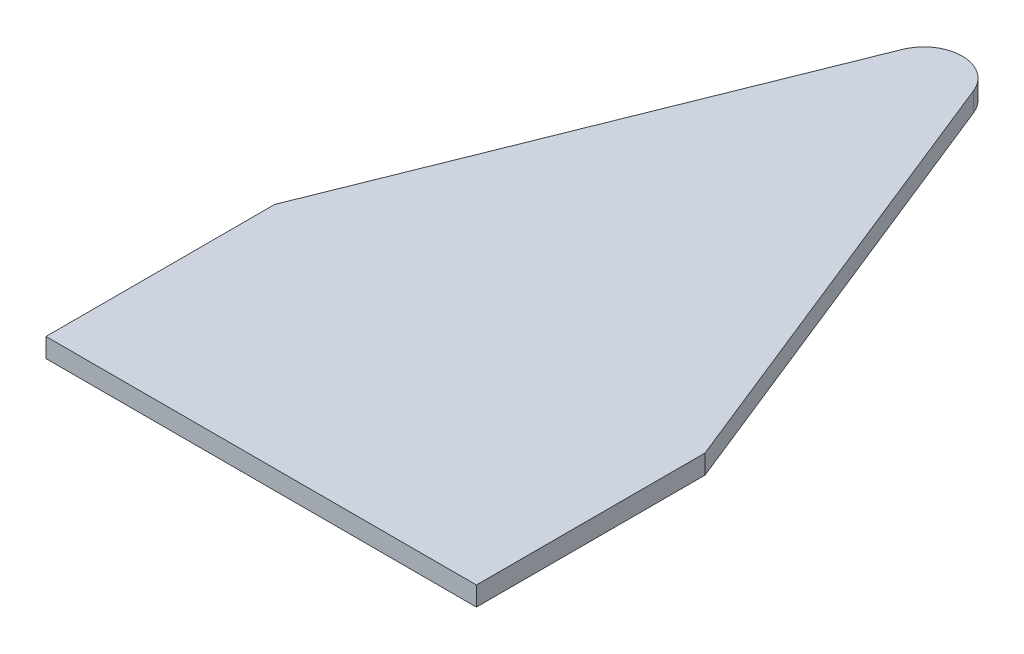
SolidWorks part; units mm, degrees
ref_plane "Front Plane" through (0, 0, 0) normal (0, 0, 1) x (1, 0, 0)
ref_plane "Top Plane" through (0, 0, 0) normal (0, 1, 0) x (1, 0, 0)
ref_plane "Right Plane" through (0, 0, 0) normal (1, 0, 0) x (0, 0, -1)
sketch "Sketch1" plane through (0, 0, 0) normal (0, 1, 0) x (1, 0, 0)
  line L0 (0, 37.846) -> (0, 215.646)
  line L1 (-71.247, -37.846) -> (71.247, -37.846)
  line L2 (-71.247, -37.846) -> (-71.247, 37.846)
  line L3 (-71.247, 37.846) -> (71.247, 37.846)
  line L4 (71.247, -37.846) -> (71.247, 37.846)
  line L5 (-71.247, -37.846) -> (71.247, 37.846) construction
  line L6 (-71.247, 37.846) -> (71.247, -37.846) construction
  line L7 (0, 215.646) -> (-71.247, 37.846)
  line L8 (71.247, 37.846) -> (0, 215.646)
  point P0 (0, 0)
  dimension "D1" = 75.692
  dimension "D2" = 142.494
  dimension "D3" = 177.8
extrude "Boss-Extrude2" add sketch "Sketch1" along normal blind 6.35 contours L0 L7 L3 | L3 L8 L0 | L1 L4 L3 L2
fillet "Fillet4" radius 12.7 1 edges at (0, 3.175, -215.646)
